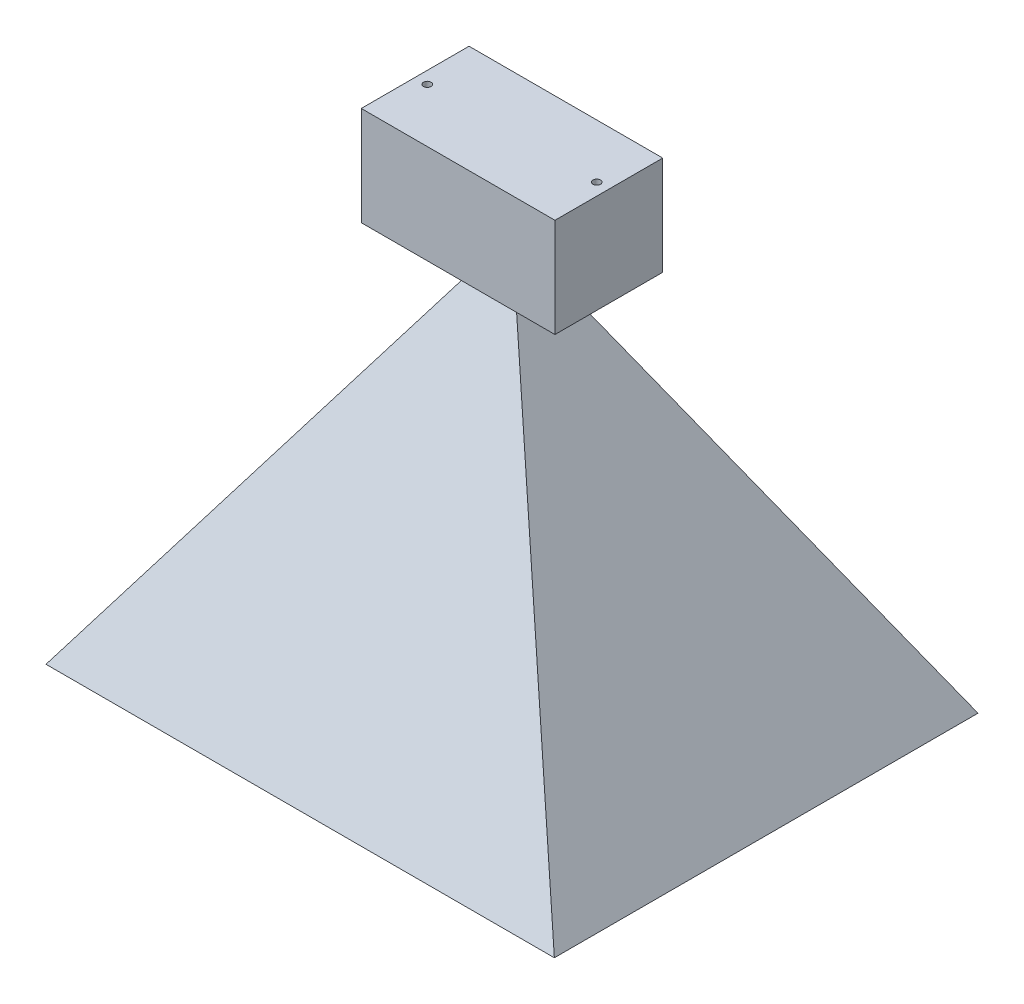
SolidWorks part; units mm, degrees
ref_plane "Front Plane" through (0, 0, 0) normal (0, 0, 1) x (1, 0, 0)
ref_plane "Top Plane" through (0, 0, 0) normal (0, 1, 0) x (1, 0, 0)
ref_plane "Right Plane" through (0, 0, 0) normal (1, 0, 0) x (0, 0, -1)
ref_plane "distance of measurement" through (0, 114.3, 0) normal (0, 1, 0) x (1, 0, 0)
sketch "Sketch1" plane through (0, 0, 0) normal (0, 1, 0) x (1, 0, 0)
  line L1 (-76.2, -63.5) -> (76.2, -63.5)
  line L2 (-76.2, -63.5) -> (-76.2, 63.5)
  line L3 (-76.2, 63.5) -> (76.2, 63.5)
  line L4 (76.2, -63.5) -> (76.2, 63.5)
  line L5 (-76.2, -63.5) -> (76.2, 63.5) construction
  line L6 (-76.2, 63.5) -> (76.2, -63.5) construction
  point P0 (0, 0)
  dimension "D1" = 152.4
  dimension "D2" = 127
sketch "Sketch2" plane through (0, 114.3, 0) normal (0, 1, 0) x (1, 0, 0)
  line L0 (-76.2, -63.5) -> (76.2, 63.5) construction
  line L1 (-2.4731, -2.0609) -> (2.4731, -2.0609)
  line L2 (-2.4731, -2.0609) -> (-2.4731, 2.0609)
  line L3 (-2.4731, 2.0609) -> (2.4731, 2.0609)
  line L4 (2.4731, -2.0609) -> (2.4731, 2.0609)
  line L5 (-2.4731, -2.0609) -> (2.4731, 2.0609) construction
  line L6 (-2.4731, 2.0609) -> (2.4731, -2.0609) construction
  point P0 (0, 0)
loft "FOV" add profiles "Sketch2", "Sketch1"
sketch "Sketch3" plane through (0, 114.3, 0) normal (0, 1, 0) x (1, 0, 0)
  circle A0 centre (0, 0) radius 8.509
  dimension "D1" = 17.018
extrude "camera lens" add sketch "Sketch3" along normal blind 0.254
sketch "Sketch4" plane through (0, 114.554, 0) normal (0, 1, 0) x (1, 0, 0)
  line L1 (29.0322, -16.1544) -> (-29.0322, -16.1544)
  line L2 (29.0322, -16.1544) -> (29.0322, 16.1544)
  line L3 (29.0322, 16.1544) -> (-29.0322, 16.1544)
  line L4 (-29.0322, -16.1544) -> (-29.0322, 16.1544)
  line L5 (29.0322, -16.1544) -> (-29.0322, 16.1544) construction
  line L6 (29.0322, 16.1544) -> (-29.0322, -16.1544) construction
  point P0 (0, 0)
  dimension "D1" = 58.0644
  dimension "D2" = 32.3088
extrude "camera holder" add sketch "Sketch4" along normal blind 29.6672
ref_point "centre of vision"
ref_point "direction reference"
sketch "reference points sketch" plane through (0, 0, 0) normal (0, -1, 0) x (1, 0, 0)
  line L0 (-76.2, 63.5) -> (76.2, 63.5) construction
  line L1 (76.2, 63.5) -> (76.2, -63.5) construction
  line L2 (76.2, -63.5) -> (-76.2, -63.5) construction
  line L3 (-76.2, -63.5) -> (-76.2, 63.5) construction
  line L4 (-76.2, 63.5) -> (76.2, -63.5) construction
  line L5 (-76.2, -63.5) -> (76.2, 63.5) construction
  point P0 (0, 63.5)
  point P1 (76.2, 0)
  point P4 (0, -63.5)
  point P7 (-76.2, 0)
  point P10 (-38.1, 0)
  point P13 (38.1, 0)
  point P14 (0, 31.75)
  point P15 (0, -31.75)
  point P16 (38.1, -31.75)
  point P17 (38.1, 31.75)
  point P20 (-38.1, 31.75)
  point P23 (-38.1, -31.75)
  point P24 (-76.2, 63.5)
  point P26 (76.2, 63.5)
  point P28 (76.2, -63.5)
  point P30 (-76.2, -63.5)
  dimension "D1" = 31.75
  dimension "D2" = 0
  dimension "D3" = 38.1
  dimension "D4" = 31.75
  dimension "D5" = 31.75
  dimension "D6" = 38.1
  dimension "D7" = 38.1
  dimension "D8" = 31.75
  dimension "D9" = 38.1
  dimension "D10" = 31.75
  dimension "D11" = 38.1
  dimension "D12" = 38.1
ref_point "direction reference 0"
ref_point "direction reference 1"
ref_point "direction reference 2"
ref_point "direction reference 3"
ref_point "direction reference 4"
ref_point "direction reference 5"
ref_point "direction reference 6"
ref_point "direction reference 7"
ref_point "direction reference 8"
ref_point "direction reference 9"
ref_point "direction reference 10"
ref_point "direction reference 11"
ref_point "direction reference 12"
ref_point "direction reference 13"
ref_point "direction reference 14"
ref_point "direction reference 15"
hole_wizard "#4-40 Tapped Hole1" positions "Sketch6" profile "Sketch5" tap size "#4-40" standard "ANSI Inch"
sketch "Sketch6" plane through (0, 144.2212, 0) normal (0, 1, 0) x (1, 0, 0)
  point P0 (-25.4, 0)
  point P2 (25.4, 0)
  dimension "D1" = 25.4
  dimension "D2" = 25.4
sketch "Sketch5" plane through (-25.4, 144.2212, 0) normal (1, 0, 0) x (0, 0, 1)
  line L0 (0, 0) -> (0, 29.6672)
  line L1 (0, 29.6672) -> (1.1303, 29.6672)
  line L2 (1.1303, 29.6672) -> (1.1303, 0)
  line L5 (1.1303, 0) -> (0, 0)
  line L11 (0, -6.35) -> (0, 107.95) construction
  dimension "Thru Tap Drill Dia." = 2.2606
  dimension "Thru Tap Drill Depth" = 29.6672
cosmetic thread "Hole Thread1" parameters "D2"=2.8448
cosmetic thread "Hole Thread2" parameters "D2"=2.8448
